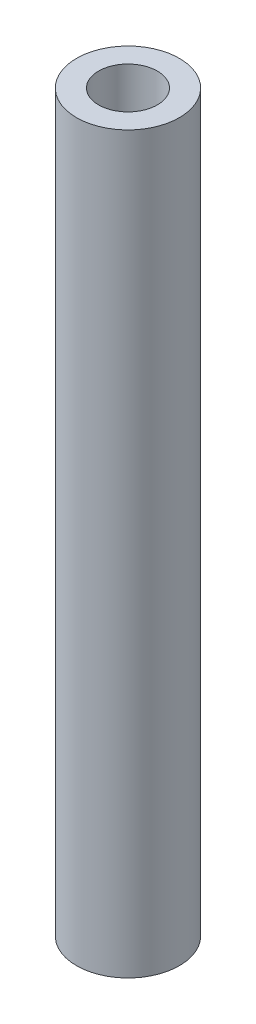
SolidWorks part; units mm, degrees
material "1060 合金"
ref_plane "前视基准面" through (0, 0, 0) normal (0, 0, 1) x (1, 0, 0)
ref_plane "上视基准面" through (0, 0, 0) normal (0, 1, 0) x (1, 0, 0)
ref_plane "右视基准面" through (0, 0, 0) normal (1, 0, 0) x (0, 0, -1)
sketch "草图1" plane through (0, 0, 0) normal (0, 1, 0) x (1, 0, 0)
  circle A0 centre (0, 0) radius 2
  circle A1 centre (0, 0) radius 3.5
  dimension "D1" = 4
  dimension "D2" = 7
extrude "凸台-拉伸1" add sketch "草图1" along normal blind 50
